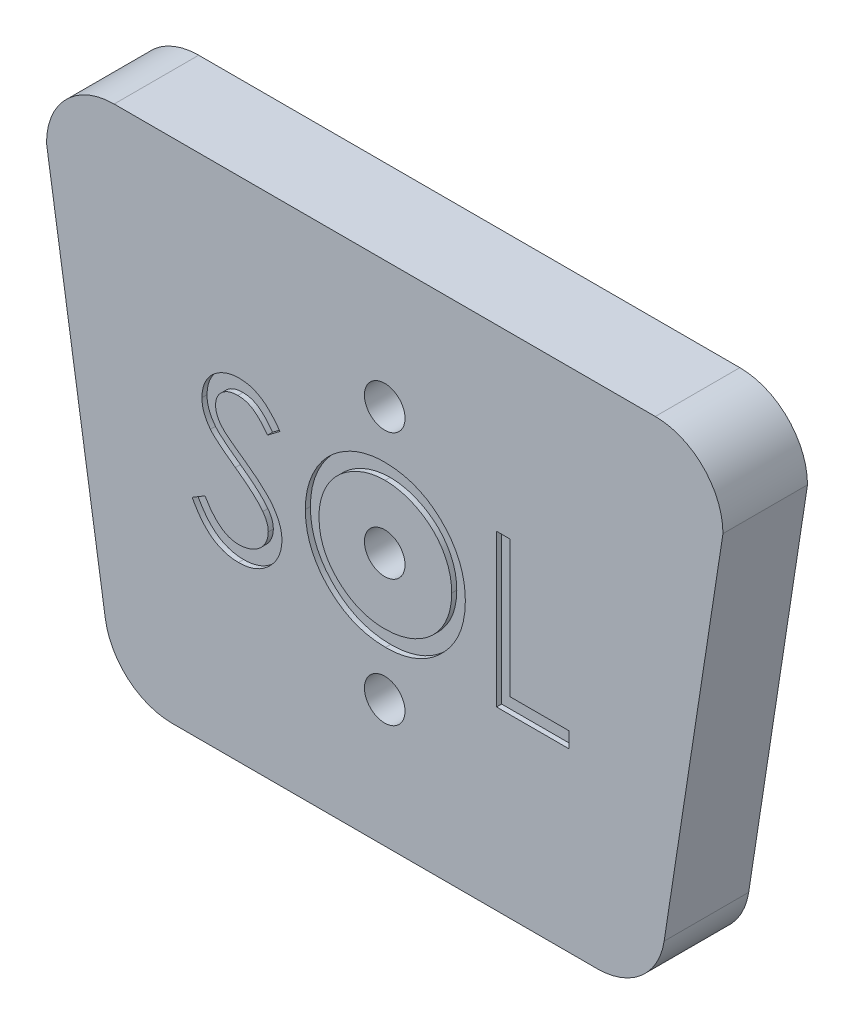
SolidWorks part; units mm, degrees
ref_plane "Front Plane" through (0, 0, 0) normal (0, 0, 1) x (1, 0, 0)
ref_plane "Top Plane" through (0, 0, 0) normal (0, 1, 0) x (1, 0, 0)
ref_plane "Right Plane" through (0, 0, 0) normal (1, 0, 0) x (0, 0, -1)
sketch "Sketch2" plane through (0, 0, 0) normal (0, 0, 1) x (1, 0, 0)
  line L0 (20, -150) -> (180, -150)
  line L1 (40, 0) -> (160, 0)
  line L3 (40, -150) -> (160, -150)
  line L6 (180, 0) -> (20, 0)
  line L8 (0, -20) -> (20, -150)
  line L9 (200, -20) -> (180, -150)
  arc A4 (200, -20) -> (180, 0) centre (180, -20) ccw
  arc A5 (0, -20) -> (20, 0) centre (20, -20) cw
  point P2 (200, 0)
  point P7 (0, -150)
  point P12 (200, 0)
  point P15 (0, 0)
  point P21 (0, 0)
  dimension "D3" = 20
  dimension "D1" = 200
  dimension "D2" = 150
extrude "Boss-Extrude1" add sketch "Sketch2" along normal blind 25 contours A5 L8 L0 L9 A4 L6 L1
fillet "Fillet2" radius 20 2 edges at (180, -150, 12.5) (20, -150, 12.5)
sketch "Sketch10" plane through (0, 0, 25) normal (0, 0, 1) x (1, 0, 0)
  line L0 (100, 0) -> (100, -150) construction
  line L1 (180, 0) -> (20, 0) construction
  line L2 (37.1584, -150) -> (162.8416, -150) construction
  line L3 (100, 0) -> (100, -75) construction
  line L4 (100, -75) -> (100, -150) construction
  line L5 (100, 0) -> (100, -75) construction
  circle A0 centre (100, -75) radius 6
  circle A1 centre (100, -112.5) radius 6
  circle A2 centre (100, -37.5) radius 6
extrude "Cut-Extrude6" cut sketch "Sketch10" against normal blind 12
sketch "Sketch11" plane through (0, 0, 13) normal (0, 0, 1) x (1, 0, 0)
  circle A0 centre (100, -37.5) radius 3
  circle A1 centre (100, -75) radius 3
  circle A2 centre (100, -112.5) radius 3
extrude "Cut-Extrude7" cut sketch "Sketch11" against normal through all
sketch "Sketch13" plane through (0, 0, 25) normal (0, 0, 1) x (1, 0, 0)
  text T0 "SOL" font "Century Gothic" height 45
extrude "Cut-Extrude8" cut sketch "Sketch13" against normal blind 1.5
